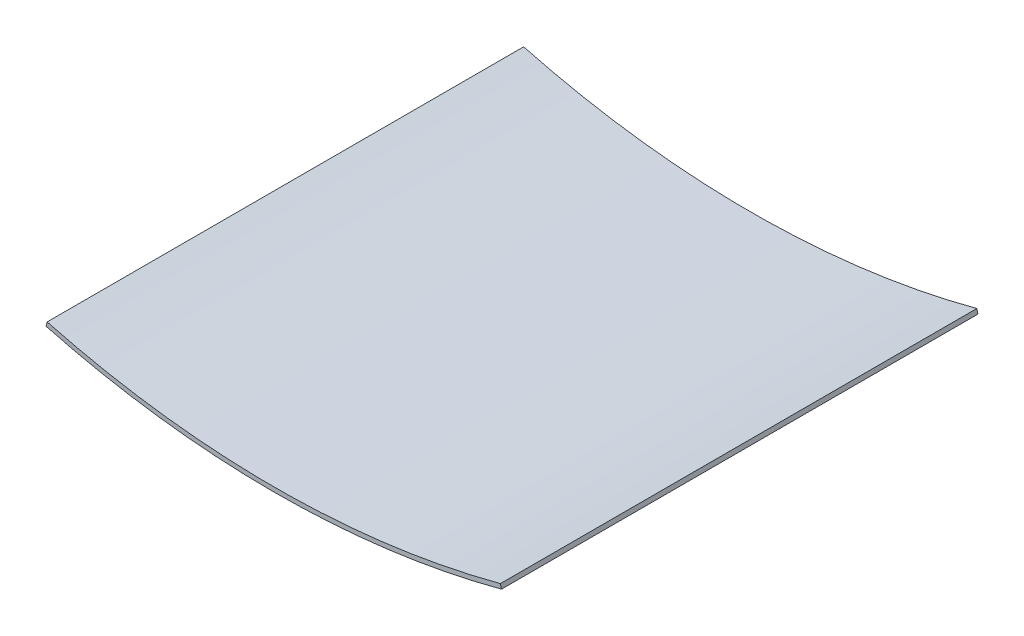
SolidWorks part; units mm, degrees
ref_plane "Front Plane" through (0, 0, 0) normal (0, 0, 1) x (1, 0, 0)
ref_plane "Top Plane" through (0, 0, 0) normal (0, 1, 0) x (1, 0, 0)
ref_plane "Right Plane" through (0, 0, 0) normal (1, 0, 0) x (0, 0, -1)
sketch "Sketch1" plane through (0, 0, 0) normal (0, 0, 1) x (1, 0, 0)
  line L0 (-195, 25.4) -> (195, 25.4) construction
  line L1 (0, 25.4) -> (0, 0) construction
  arc A0 (-195, 25.4) -> (195, 25.4) centre (0, 761.2236) ccw
  dimension "D1" = 390
  dimension "D2" = 25.4
extrude "Extrude-Thin1" add sketch "Sketch1" along normal blind 410 thin
